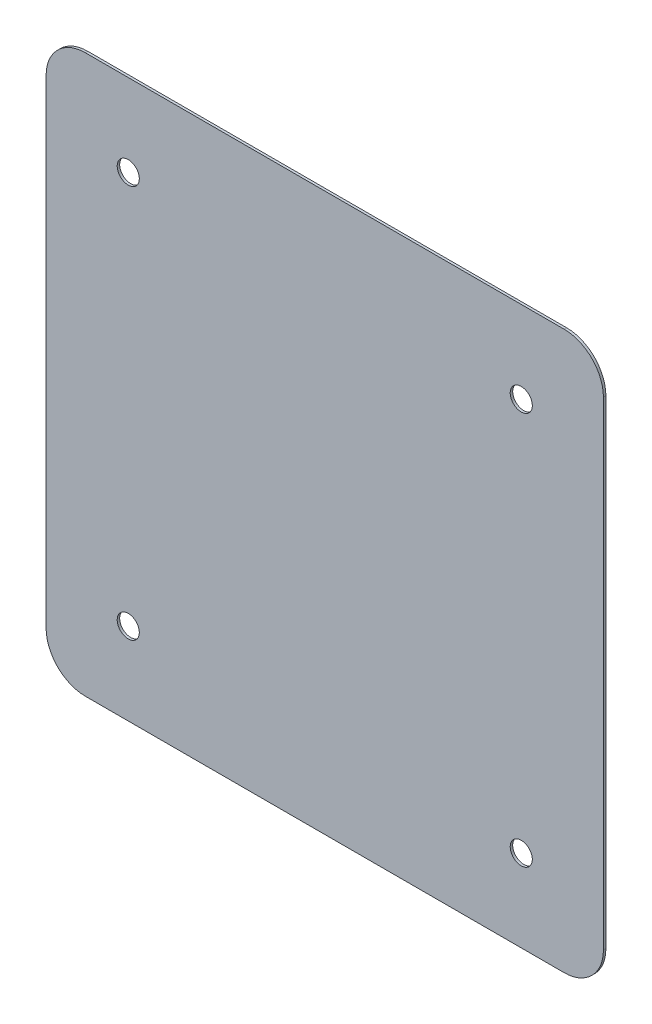
SolidWorks part; units mm, degrees
ref_plane "Front Plane" through (0, 0, 0) normal (0, 0, 1) x (1, 0, 0)
ref_plane "Top Plane" through (0, 0, 0) normal (0, 1, 0) x (1, 0, 0)
ref_plane "Right Plane" through (0, 0, 0) normal (1, 0, 0) x (0, 0, -1)
sketch "Sketch1" plane through (0, 0, 0) normal (0, 0, 1) x (1, 0, 0)
  line L0 (-77.343, 90.043) -> (77.343, 90.043)
  line L1 (90.043, 77.343) -> (90.043, -77.343)
  line L2 (77.343, -90.043) -> (-77.343, -90.043)
  line L3 (-90.043, -77.343) -> (-90.043, 77.343)
  arc A0 (77.343, 90.043) -> (90.043, 77.343) centre (77.343, 77.343) cw
  arc A1 (90.043, -77.343) -> (77.343, -90.043) centre (77.343, -77.343) cw
  arc A2 (-77.343, -90.043) -> (-90.043, -77.343) centre (-77.343, -77.343) cw
  arc A3 (-90.043, 77.343) -> (-77.343, 90.043) centre (-77.343, 77.343) cw
  circle A4 centre (-63.5, 63.5) radius 3.57
  circle A9 centre (63.5, 63.5) radius 3.57
  circle A34 centre (63.5, -63.5) radius 3.57
  circle A39 centre (-63.5, -63.5) radius 3.57
  circle A40 centre (-38.1, 38.1) radius 3.57 [skipped]
  circle A41 centre (-12.7, 38.1) radius 3.57 [skipped]
  circle A42 centre (12.7, 38.1) radius 3.57 [skipped]
  circle A43 centre (38.1, -38.1) radius 3.57 [skipped]
  circle A44 centre (38.1, -63.5) radius 3.57 [skipped]
  circle A45 centre (12.7, -63.5) radius 3.57 [skipped]
  circle A46 centre (-12.7, -63.5) radius 3.57 [skipped]
  circle A47 centre (-38.1, -63.5) radius 3.57 [skipped]
  circle A48 centre (-63.5, -38.1) radius 3.57 [skipped]
  circle A49 centre (-63.5, -12.7) radius 3.57 [skipped]
  circle A50 centre (-63.5, 12.7) radius 3.57 [skipped]
  circle A51 centre (-63.5, 38.1) radius 3.57 [skipped]
  circle A52 centre (-38.1, 63.5) radius 3.57 [skipped]
  circle A53 centre (12.7, 63.5) radius 3.57 [skipped]
  circle A54 centre (-12.7, 63.5) radius 3.57 [skipped]
  circle A55 centre (38.1, 63.5) radius 3.57 [skipped]
  circle A56 centre (38.1, 38.1) radius 3.57 [skipped]
  circle A57 centre (38.1, 12.7) radius 3.57 [skipped]
  circle A58 centre (38.1, -12.7) radius 3.57 [skipped]
  circle A59 centre (63.5, -38.1) radius 3.57 [skipped]
  circle A60 centre (63.5, -12.7) radius 3.57 [skipped]
  circle A61 centre (63.5, 12.7) radius 3.57 [skipped]
  circle A62 centre (12.7, 12.7) radius 3.57 [skipped]
  circle A63 centre (-12.7, 12.7) radius 3.57 [skipped]
  circle A64 centre (-38.1, 12.7) radius 3.57 [skipped]
  circle A65 centre (-38.1, -12.7) radius 3.57 [skipped]
  circle A66 centre (-12.7, -12.7) radius 3.57 [skipped]
  circle A67 centre (12.7, -12.7) radius 3.57 [skipped]
  circle A68 centre (12.7, -38.1) radius 3.57 [skipped]
  circle A69 centre (-12.7, -38.1) radius 3.57 [skipped]
  circle A70 centre (-38.1, -38.1) radius 3.57 [skipped]
  circle A71 centre (63.5, 38.1) radius 3.57 [skipped]
  dimension "D1" = 7.14
  dimension "D2" = 6
  dimension "D3" = 6
extrude "Boss-Extrude1" add sketch "Sketch1" along normal blind 0.8
